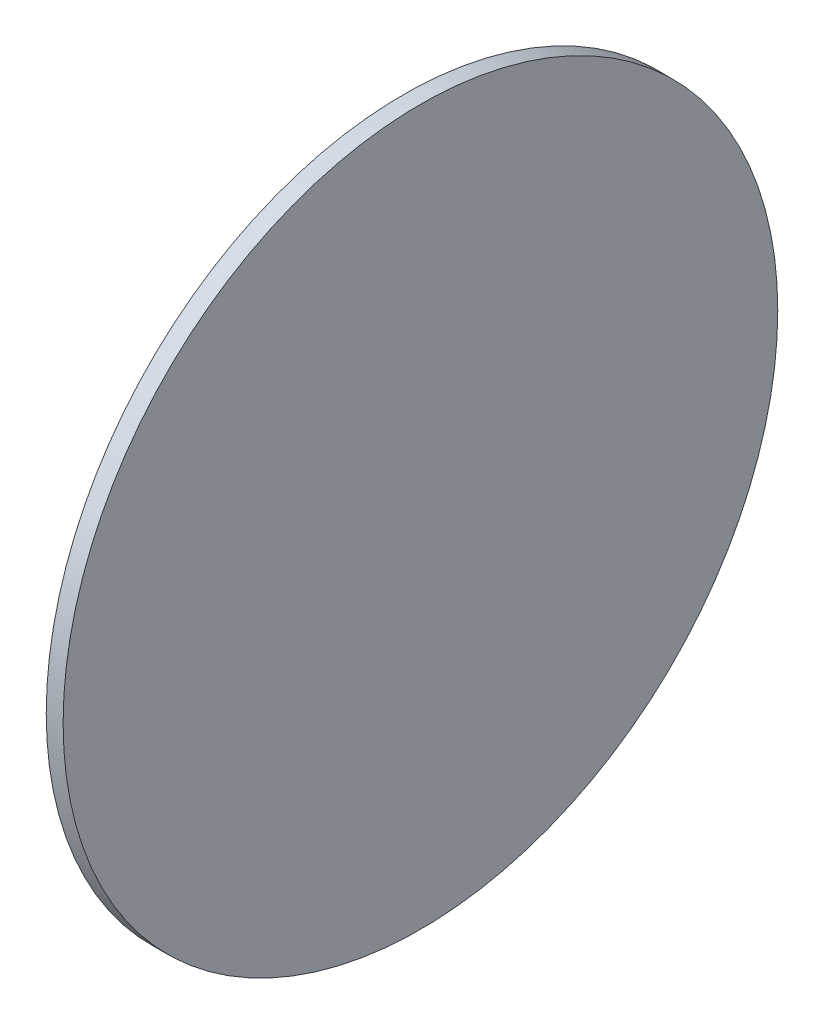
SolidWorks part; units mm, degrees
ref_plane "Plan de face" through (0, 0, 0) normal (0, 0, 1) x (1, 0, 0)
ref_plane "Plan de dessus" through (0, 0, 0) normal (0, 1, 0) x (1, 0, 0)
ref_plane "Plan de droite" through (0, 0, 0) normal (1, 0, 0) x (0, 0, -1)
sketch "Esquisse1" plane through (0, 0, 0) normal (1, 0, 0) x (0, 0, -1)
  circle A0 centre (0, 0) radius 317.5
extrude "Boss.-Extru.1" add sketch "Esquisse1" along normal blind 15
